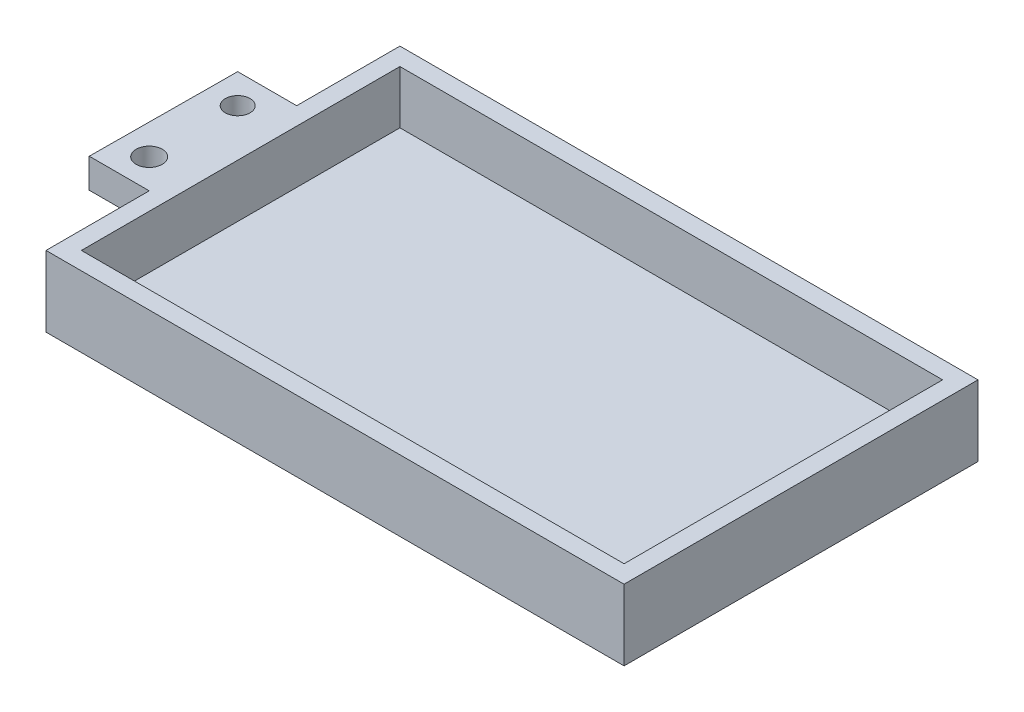
SolidWorks part; units mm, degrees
ref_plane "前视基准面" through (0, 0, 0) normal (0, 0, 1) x (1, 0, 0)
ref_plane "上视基准面" through (0, 0, 0) normal (0, 1, 0) x (1, 0, 0)
ref_plane "右视基准面" through (0, 0, 0) normal (1, 0, 0) x (0, 0, -1)
sketch "草图1" plane through (0, 0, 0) normal (0, 1, 0) x (1, 0, 0)
  line L0 (49, -30) -> (-49, -30)
  line L1 (-49, 30) -> (49, 30) construction
  line L2 (-49, 30) -> (-49, -30) construction
  line L3 (-49, -30) -> (49, -30) construction
  line L4 (49, 30) -> (49, -30) construction
  line L5 (0, -30) -> (0, 30) construction
  line L6 (-49, 0) -> (49, 0) construction
  line L7 (-39, -5) -> (-59, -5) construction
  line L8 (-39, -5) -> (-39, 5) construction
  line L9 (-39, 5) -> (-59, 5) construction
  line L11 (-49, -30) -> (-49, -12.5)
  line L12 (-39, 0) -> (-59, 0) construction
  line L17 (-59, 5) -> (-49, 5) construction
  line L18 (-59, 5) -> (-59, -5) construction
  line L19 (-49, -30) -> (-49, -5) construction
  line L23 (-49, 5) -> (-49, 30) construction
  line L24 (-49, 30) -> (49, 30)
  line L25 (49, 30) -> (49, -30)
  line L26 (-59, -5) -> (-49, -5) construction
  line L27 (-49, 5) -> (-49, -5) construction
  line L28 (-54, -5) -> (-54, 5) construction
  line L29 (-59, 0) -> (-49, 0) construction
  line L30 (-59, 12.5) -> (-49, 12.5) construction
  line L31 (-59, 12.5) -> (-59, -12.5) construction
  line L32 (-59, -12.5) -> (-49, -12.5) construction
  line L33 (-49, 12.5) -> (-49, -12.5) construction
  line L34 (-54, -12.5) -> (-54, 12.5) construction
  line L35 (-59, 0) -> (-49, 0) construction
  line L36 (-59, 12.5) -> (-49, 12.5) construction
  line L37 (-59, 12.5) -> (-59, 2.5) construction
  line L38 (-59, 2.5) -> (-49, 2.5) construction
  line L39 (-49, 12.5) -> (-49, 2.5) construction
  line L40 (-54, 2.5) -> (-54, 12.5) construction
  line L41 (-59, 7.5) -> (-49, 7.5) construction
  line L42 (-59, -12.5) -> (-49, -12.5) construction
  line L43 (-59, -12.5) -> (-59, -2.5) construction
  line L44 (-59, -2.5) -> (-49, -2.5) construction
  line L45 (-49, -12.5) -> (-49, -2.5) construction
  line L46 (-54, -2.5) -> (-54, -12.5) construction
  line L47 (-59, -7.5) -> (-49, -7.5) construction
  line L48 (-49, -12.5) -> (-59.1681, -12.5)
  line L49 (-59.1681, -12.5) -> (-59, 12.5)
  line L50 (-59, 12.5) -> (-49, 12.5)
  line L51 (-49, 12.5) -> (-49, 30)
  circle A2 centre (-54, 7.5) radius 2.1
  circle A3 centre (-54, -7.5) radius 2.2201
  point P0 (0, 0)
  point P7 (-54, 0)
  point P128 (-54, -7.5)
  point P154 (-54, 7.5)
  point P156 (-54, 0)
  dimension "D4" = 25
  dimension "D1" = 98
  dimension "D2" = 60
  dimension "D3" = 20
  dimension "D5" = 10
  dimension "D6" = 10
extrude "凸台-拉伸1" add sketch "草图1" along normal blind 12
sketch "草图2" plane through (0, 12, 0) normal (0, 1, 0) x (1, 0, 0)
  line L1 (-46, 27) -> (46, 27)
  line L2 (-46, 27) -> (-46, -27)
  line L3 (-46, -27) -> (46, -27)
  line L4 (46, 27) -> (46, -27)
  line L5 (0, -27) -> (0, 27) construction
  line L6 (-46, 0) -> (46, 0) construction
  point P0 (0, 0)
  dimension "D1" = 92
  dimension "D2" = 54
extrude "切除-拉伸1" cut sketch "草图2" against normal offset from surface (9 mm away) 3 up to face at (-54, 0, -5.4)
sketch "草图3" plane through (0, 0, 0) normal (0, -1, 0) x (1, 0, 0)
  line L1 (-59.1681, 12.5) -> (-49, 12.5)
  line L2 (-59.1681, 12.5) -> (-59.1681, -12.5)
  line L3 (-59.1681, -12.5) -> (-49, -12.5)
  line L4 (-49, 12.5) -> (-49, -12.5)
  line L5 (-54.084, -12.5) -> (-54.084, 12.5) construction
  line L6 (-59.1681, 0) -> (-49, 0) construction
  point P216 (-54.084, 0)
extrude "切除-拉伸2" cut sketch "草图3" against normal blind 7
ref_plane "基准面1" through (0, 0, 0) normal (0, 0, 1) x (1, 0, 0)
sketch "草图5" plane through (0, 0, 0) normal (0, 0, 1) x (1, 0, 0)
  line L0 (-56.2201, 7) -> (-49, 1.8361)
  line L1 (-49, 12) -> (-49, 0) construction
rib "筋1" sketch "草图5" sketch "草图5" thickness 5 extrusion direction parallel to sketch draft on no parameters "D1"=5
